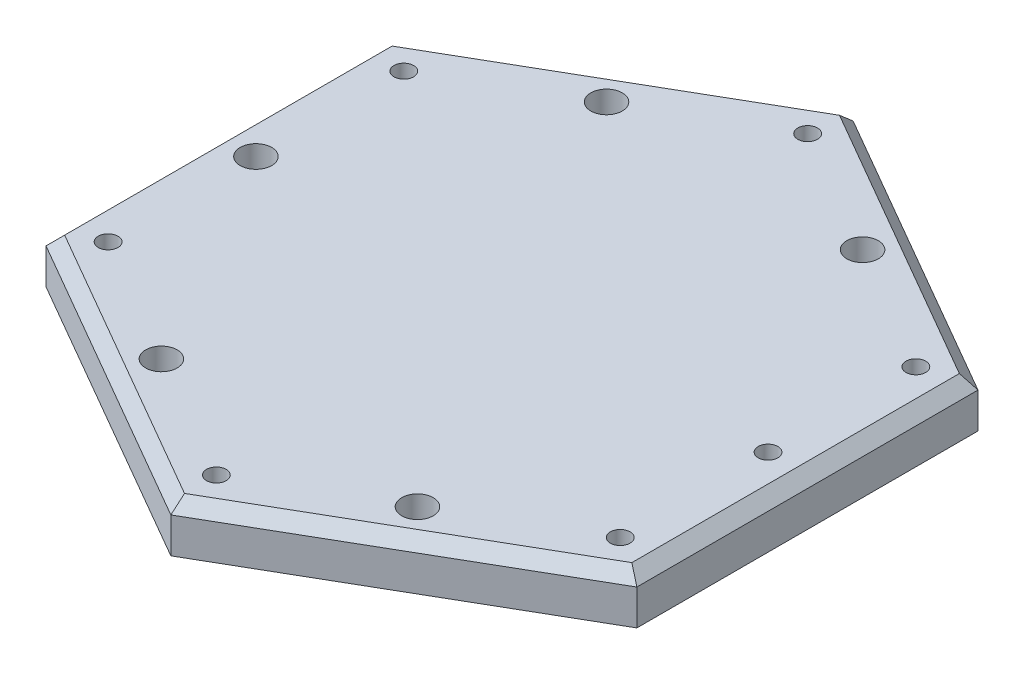
SolidWorks part; units mm, degrees
ref_plane "前基準面" through (0, 0, 0) normal (0, 0, 1) x (1, 0, 0)
ref_plane "上基準面" through (0, 0, 0) normal (0, 1, 0) x (1, 0, 0)
ref_plane "右基準面" through (0, 0, 0) normal (1, 0, 0) x (0, 0, -1)
sketch "草圖2" plane through (0, 0, 0) normal (0, 1, 0) x (1, 0, 0)
  line L1 (0, 86.6025) -> (-75, 43.3013)
  line L2 (-75, 43.3013) -> (-75, -43.3013)
  line L3 (-75, -43.3013) -> (0, -86.6025)
  line L4 (0, -86.6025) -> (75, -43.3013)
  line L5 (75, -43.3013) -> (75, 43.3013)
  line L6 (75, 43.3013) -> (0, 86.6025)
  circle A0 centre (0, 0) radius 75 construction
  dimension "D1" = 150
extrude "填料-伸長2" add sketch "草圖2" along normal blind 12
chamfer "導角1" distance 3 angle 45 6 edges at (75, 12, 0) (37.5, 12, 64.9519) (-37.5, 12, 64.9519) (-75, 12, 0) (-37.5, 12, -64.9519) (37.5, 12, -64.9519)
sketch "草圖3" plane through (0, 12, 0) normal (0, 1, 0) x (1, 0, 0)
  line L0 (-65, 0) -> (65, 0)
  line L1 (-32.5, -56.5) -> (32.5, -56.5)
  line L2 (-32.5, -56.5) -> (-32.5, 56.5)
  line L3 (-32.5, 56.5) -> (32.5, 56.5)
  line L4 (32.5, -56.5) -> (32.5, 56.5)
  line L5 (-32.5, -56.5) -> (32.5, 56.5) construction
  line L6 (-32.5, 56.5) -> (32.5, -56.5) construction
  line L7 (0, 75.0555) -> (-65, 37.5278)
  line L8 (-65, 37.5278) -> (-65, -37.5278)
  line L9 (-65, -37.5278) -> (0, -75.0555)
  line L10 (0, -75.0555) -> (65, -37.5278)
  line L11 (65, -37.5278) -> (65, 37.5278)
  line L12 (65, 37.5278) -> (0, 75.0555)
  circle A0 centre (0, 0) radius 65 construction
  point P0 (0, 0)
  dimension "D1" = 130
  dimension "D2" = 65
  dimension "D3" = 113
  dimension "D4" = 75.0555
hole_wizard "M6 螺紋孔2" positions "3D草圖2" profile "草圖7" tap size "M6" standard "ISO" end condition through all
sketch3d "3D草圖2"
  point P0 (-65, 12, 37.5278)
  point P3 (-65, 12, -37.5278)
  point P6 (0, 12, -75.0555)
  point P9 (65, 12, -37.5278)
  point P12 (65, 12, 0)
  point P15 (0, 12, 75.0555)
  point P19 (65, 12, 37.5278)
sketch "草圖7" plane through (-65, 12, 37.5278) normal (1, 0, 0) x (0, 0, 1)
  line L0 (0, 0) -> (0, 12)
  line L1 (0, 12) -> (2.5, 12)
  line L2 (2.5, 12) -> (2.5, 0)
  line L5 (2.5, 0) -> (0, 0)
  line L11 (0, -6.35) -> (0, 107.95) construction
  dimension "砮 脸ふ苝 畖" = 5
  dimension "砮 脸ふ苝瞏 " = 12
cosmetic thread "鑽孔螺紋1"
cosmetic thread "鑽孔螺紋2"
cosmetic thread "鑽孔螺紋3"
cosmetic thread "鑽孔螺紋4"
cosmetic thread "鑽孔螺紋5"
cosmetic thread "鑽孔螺紋6"
cosmetic thread "鑽孔螺紋7"
hole_wizard "Ø8.0mm 定位孔1" positions "3D草圖3" profile "草圖9" hole size "Ø8.0" standard "ISO" end condition through all
sketch3d "3D草圖3"
  point P0 (-65, 12, 0)
  point P3 (-32.5, 12, 56.5)
  point P6 (32.5, 12, 56.5)
  point P9 (32.5, 12, -56.5)
  point P12 (-32.5, 12, -56.5)
sketch "草圖9" plane through (-65, 12, 0) normal (1, 0, 0) x (0, 0, 1)
  line L0 (0, 0) -> (0, 12)
  line L1 (0, 12) -> (4, 12)
  line L2 (4, 12) -> (4, 0)
  line L5 (4, 0) -> (0, 0)
  line L11 (0, -6.35) -> (0, 107.95) construction
  dimension "砮 ふ 畖" = 8
  dimension "砮 ふ瞏 " = 12
